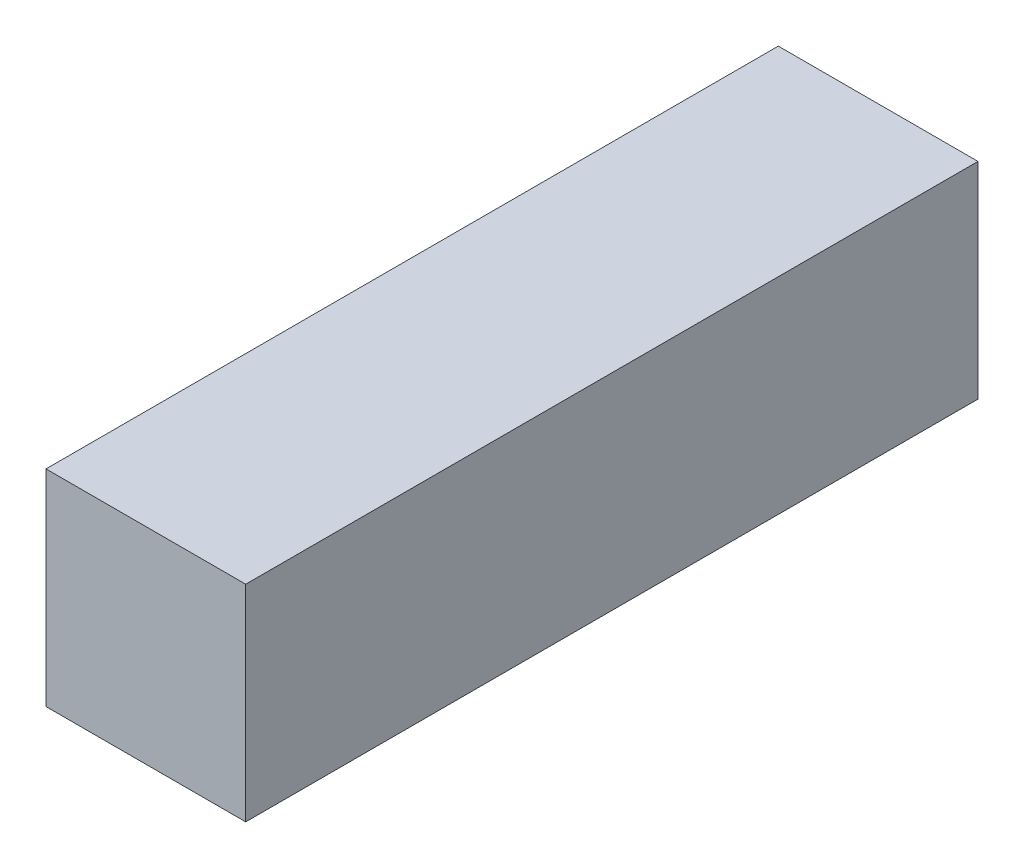
SolidWorks part; units mm, degrees
ref_plane "Front Plane" through (0, 0, 0) normal (0, 0, 1) x (1, 0, 0)
ref_plane "Top Plane" through (0, 0, 0) normal (0, 1, 0) x (1, 0, 0)
ref_plane "Right Plane" through (0, 0, 0) normal (1, 0, 0) x (0, 0, -1)
sketch "Sketch2" plane through (0, 0, 0) normal (0, 1, 0) x (1, 0, 0)
  line L3 (-1.5, -5.5) -> (1.5, -5.5)
  line L4 (-1.5, -5.5) -> (-1.5, 5.5)
  line L5 (-1.5, 5.5) -> (1.5, 5.5)
  line L6 (1.5, -5.5) -> (1.5, 5.5)
  line L7 (-1.5, -5.5) -> (1.5, 5.5) construction
  line L8 (-1.5, 5.5) -> (1.5, -5.5) construction
  point P0 (0, 0)
  dimension "D1" = 11
  dimension "D2" = 3
extrude "Boss-Extrude1" add sketch "Sketch2" along normal blind 3.0922
